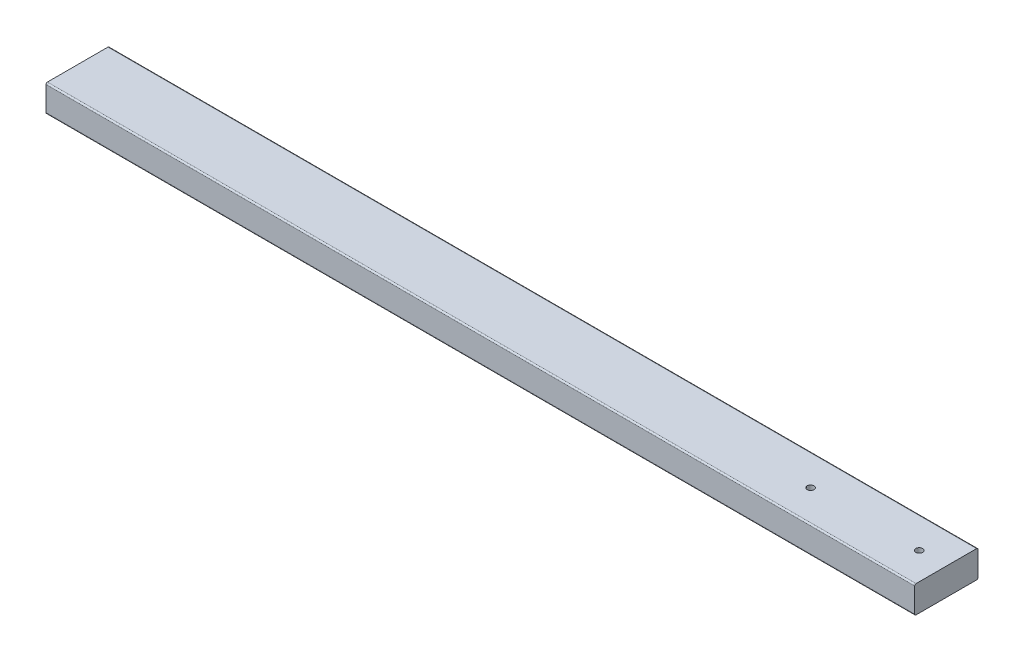
SolidWorks part; units mm, degrees
ref_plane "Front Plane" through (0, 0, 0) normal (0, 0, 1) x (1, 0, 0)
ref_plane "Top Plane" through (0, 0, 0) normal (0, 1, 0) x (1, 0, 0)
ref_plane "Right Plane" through (0, 0, 0) normal (1, 0, 0) x (0, 0, -1)
sketch "Sketch1" plane through (0, 609.6, 0) normal (1, 0, 0) x (0, 0, -1)
  line L1 (-44.45, -628.65) -> (44.45, -628.65)
  line L2 (-44.45, -628.65) -> (-44.45, -590.55)
  line L3 (-44.45, -590.55) -> (44.45, -590.55)
  line L4 (44.45, -628.65) -> (44.45, -590.55)
  line L5 (-44.45, -628.65) -> (44.45, -590.55) construction
  line L6 (-44.45, -590.55) -> (44.45, -628.65) construction
  point P0 (0, -609.6)
  dimension "D1" = 38.1
  dimension "D2" = 88.9
extrude "Boss-Extrude1" add sketch "Sketch1" along normal blind 1219.2
fillet "Fillet1" radius 2 4 edges at (609.6, 19.05, 44.45) (609.6, 19.05, -44.45) (609.6, -19.05, -44.45) (609.6, -19.05, 44.45)
other "2x4<1>"
sketch "Sketch2" plane through (0, -19.05, 0) normal (0, -1, 0) x (-1, 0, 0)
  line L1 (-1219.2, -42.45) -> (-1219.2, 42.45) construction
  circle A0 centre (-1028.7, 0) radius 4.7625
  circle A1 centre (-1181.1, 0) radius 4.7625
  point P11 (-1219.2, 0)
  dimension "D1" = 9.525
  dimension "D2" = 152.4
  dimension "D3" = 38.1
extrude "Cut-Extrude1" cut sketch "Sketch2" against normal through all
